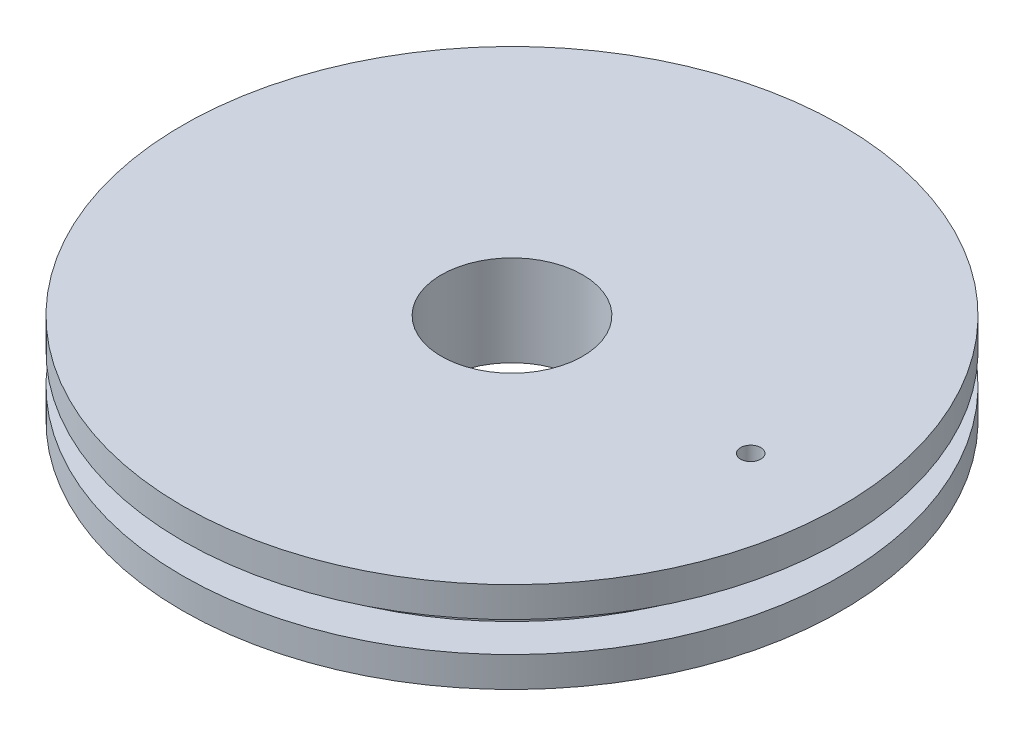
SolidWorks part; units mm, degrees
ref_plane "Front Plane" through (0, 0, 0) normal (0, 0, 1) x (1, 0, 0)
ref_plane "Top Plane" through (0, 0, 0) normal (0, 1, 0) x (1, 0, 0)
ref_plane "Right Plane" through (0, 0, 0) normal (1, 0, 0) x (0, 0, -1)
sketch "Sketch1" plane through (0, 0, 0) normal (0, 0, 1) x (1, 0, 0)
  line L2 (7, 4.5) -> (32.65, 4.5)
  line L3 (32.65, 4.5) -> (32.65, 1.5)
  line L4 (32.65, 1.5) -> (28.65, 1.5)
  line L5 (28.65, 1.5) -> (28.65, -1.5)
  line L6 (35.915, 0) -> (-35.915, 0) construction
  line L7 (32.65, -4.5) -> (32.65, -1.5)
  line L8 (32.65, -1.5) -> (28.65, -1.5)
  line L9 (7, -4.5) -> (32.65, -4.5)
  line L10 (7, 4.5) -> (7, -4.5)
  line L11 (0, 0) -> (0, 14.7507) construction
  point P4 (32.65, 3)
  point P8 (32.65, -3)
  point P14 (28.65, 0)
  dimension "D1" = 14
  dimension "D2" = 3
  dimension "D3" = 3
  dimension "D4" = 4
  dimension "D5" = 57.3
revolve "Revolve1" add sketch "Sketch1" angle 360 about L11
sketch "Sketch2" plane through (0, 4.5, 0) normal (0, 1, 0) x (1, 0, 0)
  line L0 (-4.95, 0) -> (4.95, 0) construction
  line L1 (28.65, 9.5825) -> (28.65, -17.1737) construction
  circle A0 centre (23.65, 0) radius 1
  circle A1 centre (0, 0) radius 28.65 construction
  circle A2 centre (0, 0) radius 28.65 construction
  dimension "D2" = 2
  dimension "D1" = 10
extrude "Cut-Extrude1" cut sketch "Sketch2" against normal through all
